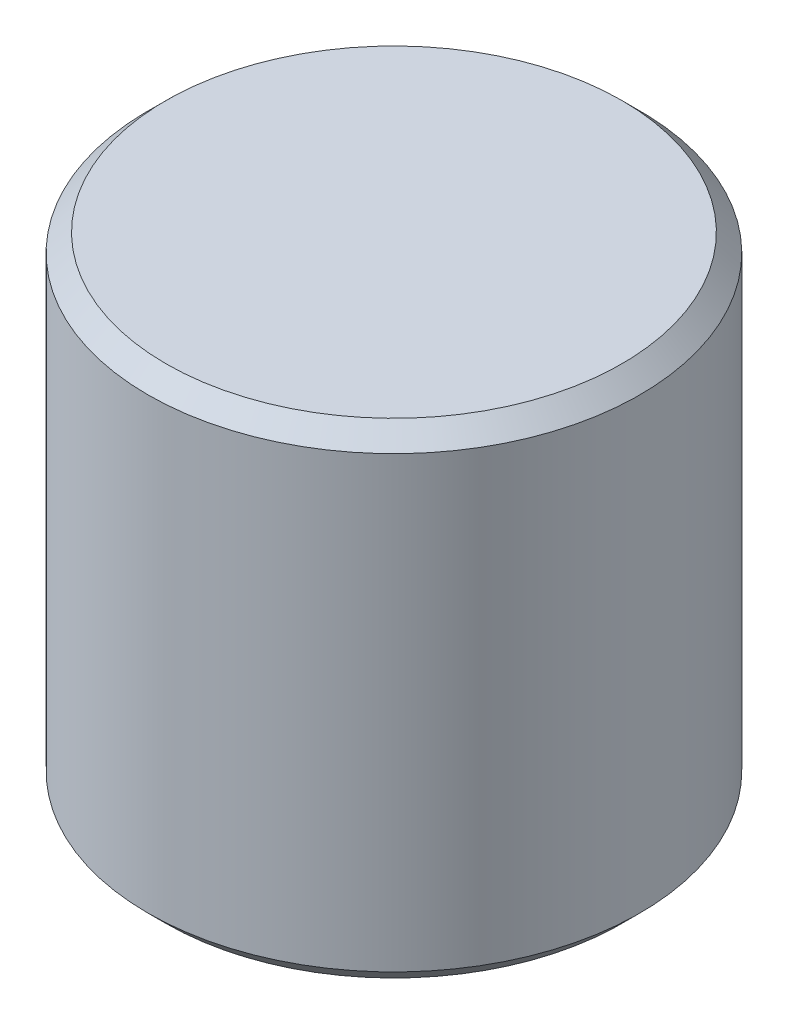
SolidWorks part; units mm, degrees
ref_plane "正面" through (0, 0, 0) normal (0, 0, 1) x (1, 0, 0)
ref_plane "平面" through (0, 0, 0) normal (0, 1, 0) x (1, 0, 0)
ref_plane "右側面" through (0, 0, 0) normal (1, 0, 0) x (0, 0, -1)
sketch "ｽｹｯﾁ1" plane through (0, 0, 0) normal (0, 0, 1) x (1, 0, 0)
  line L0 (5.5, 0) -> (6.35, 0)
  line L1 (6.85, 0.5) -> (6.85, 13)
  line L2 (6.35, 13.5) -> (0, 13.5)
  line L3 (0, 13.5) -> (0, 0) construction
  line L4 (5.5, 0) -> (5.5, 2)
  line L5 (5.5, 2) -> (3.05, 2)
  line L6 (3.05, 2) -> (3.05, 11.6)
  line L7 (3.05, 11.6) -> (0, 11.6)
  line L8 (0, 13.5) -> (0, 11.6)
  line L9 (6.85, 13) -> (6.35, 13.5)
  line L10 (6.35, 0) -> (6.85, 0.5)
  point P4 (6.85, 0)
  point P5 (6.85, 13.5)
  dimension "D1" = 6.85
  dimension "D2" = 13.5
  dimension "D3" = 11.6
  dimension "D4" = 2
  dimension "D5" = 3.05
  dimension "D6" = 5.5
revolve "回転1" add sketch "ｽｹｯﾁ1" angle 360 about L3
sketch "ｽｹｯﾁ2" [suppressed] plane through (0, 13.5, 0) normal (0, 1, 0) x (1, 0, 0)
  line L0 (0, 6.35) -> (0, 0) construction
  line L1 (0, 5.5) -> (0, 4.5)
  circle A0 centre (0, 0) radius 6.35 construction
  arc A1 (0, 4.5) -> (0, 5.5) centre (0, 5) ccw
  circle A2 centre (0, 0) radius 6.85 construction
  dimension "D1" = 5
  dimension "D2" = 1
revolve "ｶｯﾄ - 回転3" [suppressed] cut sketch "ｽｹｯﾁ2" angle 360 about L0
sketch "ｽｹｯﾁ3" [suppressed] plane through (0, 0, 0) normal (0, 0, 1) x (1, 0, 0)
  line L0 (0, 13.5) -> (0, 0) construction
  line L1 (0.5, 13.5) -> (-0.5, 13.5) construction
  line L2 (-6.35, 0) -> (6.35, 0) construction
  circle A0 centre (0, 5) radius 1.5
  dimension "D1" = 5
extrude "ｶｯﾄ - 押し出し1" [suppressed] cut sketch "ｽｹｯﾁ3" along normal blind 10
